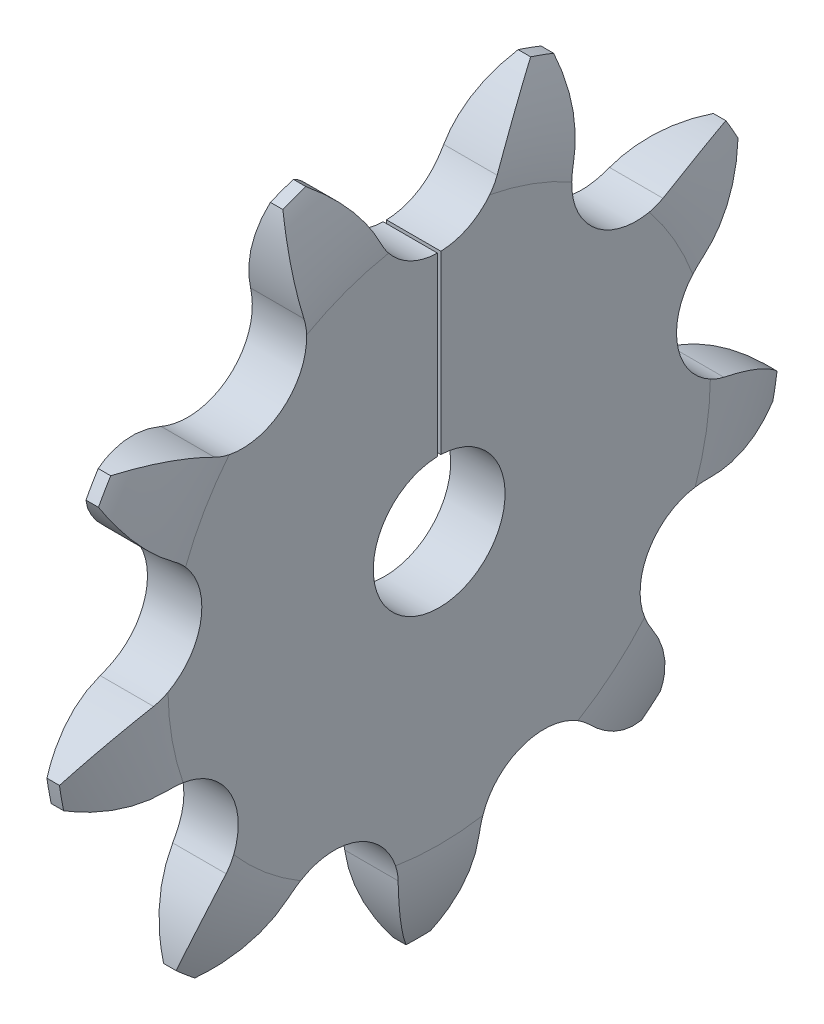
SolidWorks part; units mm, degrees
ref_plane "Plano frontal" through (0, 0, 0) normal (0, 0, 1) x (1, 0, 0)
ref_plane "Plano superior" through (0, 0, 0) normal (0, 1, 0) x (1, 0, 0)
ref_plane "Plano direito" through (0, 0, 0) normal (1, 0, 0) x (0, 0, -1)
sketch "Esboço2" plane through (0, 0, 0) normal (0, 0, 1) x (1, 0, 0)
  line L0 (0, 0) -> (60, 0) construction
  line L1 (0, 0) -> (0, 16.4642)
  line L2 (0, 0) -> (3.3, 0)
  line L3 (3.3, 0) -> (3.3, 16.4642)
  line L4 (2.03, 22) -> (1.27, 22)
  arc A0 (0, 16.4642) -> (1.27, 22) centre (12.7, 16.4642) cw
  arc A1 (3.3, 16.4642) -> (2.03, 22) centre (-9.4, 16.4642) ccw
  dimension "D1" = 12.7
  dimension "G1" = 1.27
  dimension "G2" = 1.27
  dimension "Diameter" = 44
  dimension "Thickness" = 3.3
revolve "Revolução1" add sketch "Esboço2" angle 360 about L0
sketch "Esboço5" plane through (0, 0, 0) normal (1, 0, 0) x (0, 0, -1)
  line L0 (0, 18.6049) -> (3.5471, 16.9509) construction
  line L1 (0, 0) -> (0, 133.4326) construction
  line L2 (0, 18.6049) -> (-10, 18.6049) construction
  line L3 (0, 18.6049) -> (-3.5471, 16.9509) construction
  arc A0 (3.5471, 16.9509) -> (8.0549, 21.6807) centre (12.8186, 12.6275) cw
  arc A1 (3.5471, 16.9509) -> (-3.5471, 16.9509) centre (0, 18.6049) cw
  arc A2 (-3.5471, 16.9509) -> (-8.0549, 21.6807) centre (-12.8186, 12.6275) ccw
  arc A3 (8.0549, 21.6807) -> (-8.0549, 21.6807) centre (0, 0) ccw
  dimension "D1" = 18.6049
  dimension "D2" = 3.9137
  dimension "D4" = 10.23
  dimension "D5" = 23.1287
  dimension "D3" = 130
extrude "Corte-extrusão1" cut sketch "Esboço5" along normal through all
pattern_circular "PadrãoCircular2" count 9 over 360 about axis through (0, 0, 0) along (1, 0, 0) of "Corte-extrusão1"
sketch "Esboço6" plane through (3.3, 0, 0) normal (1, 0, 0) x (0, 0, -1)
  circle A0 centre (0, 0) radius 4
  dimension "D1" = 8
extrude "Corte-extrusão2" cut sketch "Esboço6" against normal through all
sketch "Esboço7" plane through (3.3, 0, 0) normal (1, 0, 0) x (0, 0, -1)
  line L0 (0, 0) -> (0, 22.4632) construction
  line L1 (-0.1, 0) -> (0.1, 0)
  line L2 (-0.1, 0) -> (-0.1, 30)
  line L3 (-0.1, 30) -> (0.1, 30)
  line L4 (0.1, 0) -> (0.1, 30)
  dimension "D1" = 0.2
  dimension "D2" = 30
extrude "Corte-extrusão3" cut sketch "Esboço7" against normal blind 10
